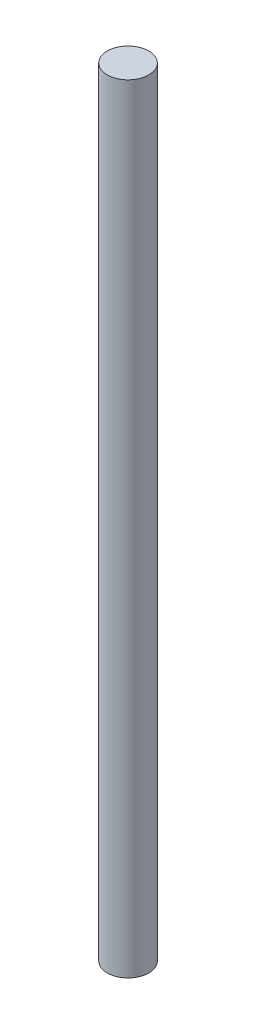
SolidWorks part; units mm, degrees
material "Tungsten"
ref_plane "Front Plane" through (0, 0, 0) normal (0, 0, 1) x (1, 0, 0)
ref_plane "Top Plane" through (0, 0, 0) normal (0, 1, 0) x (1, 0, 0)
ref_plane "Right Plane" through (0, 0, 0) normal (1, 0, 0) x (0, 0, -1)
sketch "Sketch1" plane through (0, 0, 0) normal (0, 0, 1) x (1, 0, 0)
  line L0 (0, 0) -> (-1.6, 0)
  line L1 (-1.6, 0) -> (-1.6, 60)
  line L2 (-1.6, 60) -> (0, 60)
  line L3 (0, 60) -> (0, 0)
  line L4 (0, -10.2) -> (0, 66.8) construction
  dimension "D1" = 60
  dimension "D2" = 1.6
revolve "Revolve1" add sketch "Sketch1" angle 360 about L4
